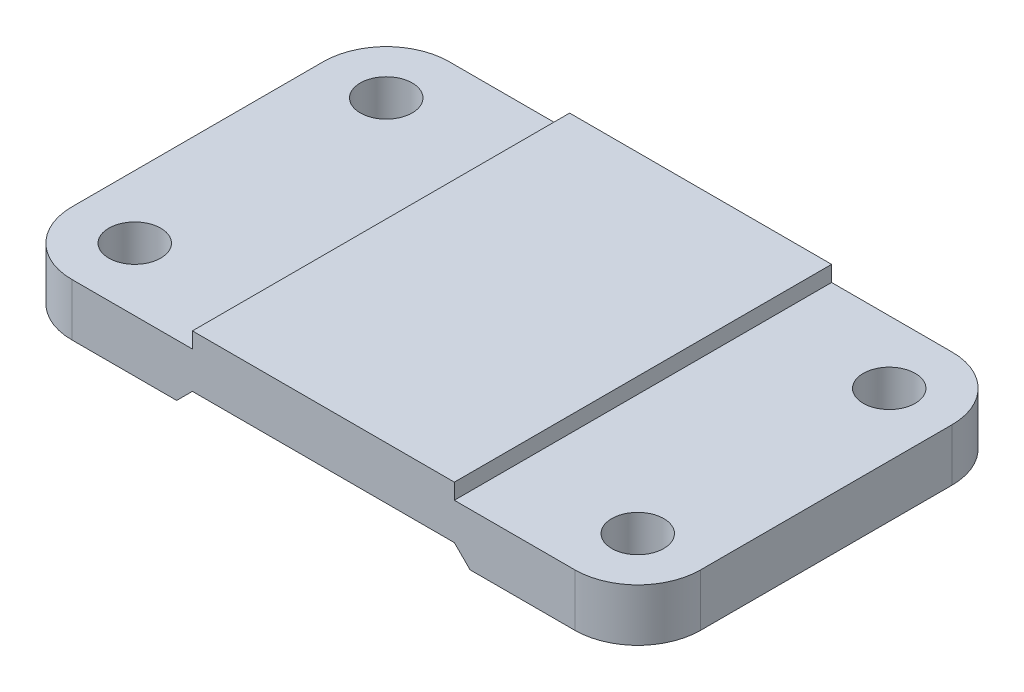
SolidWorks part; units mm, degrees
ref_plane "Front Plane" through (0, 0, 0) normal (0, 0, 1) x (1, 0, 0)
ref_plane "Top Plane" through (0, 0, 0) normal (0, 1, 0) x (1, 0, 0)
ref_plane "Right Plane" through (0, 0, 0) normal (1, 0, 0) x (0, 0, -1)
sketch "Sketch1" plane through (0, 0, 0) normal (0, 1, 0) x (1, 0, 0)
  line L0 (-111.57, 0) -> (84.1985, 0) construction
  line L1 (-60, -36) -> (60, -36)
  line L2 (-60, -36) -> (-60, 36)
  line L3 (-60, 36) -> (60, 36)
  line L4 (60, -36) -> (60, 36)
  line L5 (-60, -36) -> (60, 36) construction
  line L6 (-60, 36) -> (60, -36) construction
  line L7 (0, 48.1132) -> (0, -59.3675) construction
  circle A0 centre (-48, 24) radius 4.9597
  circle A1 centre (48, 24) radius 4.9597
  circle A2 centre (48, -24) radius 4.9597
  circle A3 centre (-48, -24) radius 4.9597
  point P0 (0, 0)
  dimension "D1" = 72
  dimension "D2" = 120
  dimension "D3" = 24
  dimension "D4" = 48
extrude "Boss-Extrude1" add sketch "Sketch1" along normal blind 10
fillet "Fillet1" radius 12 4 edges at (60, 5, 36) (-60, 5, 36) (-60, 5, -36) (60, 5, -36)
sketch "Sketch2" plane through (0, 0, 36) normal (0, 0, 1) x (1, 0, 0)
  line L0 (0, 19.0191) -> (0, -13.0598) construction
  line L1 (0, 0) -> (0, 3)
  line L2 (-48, 0) -> (48, 0) construction
  line L3 (-25, 3) -> (25, 3)
  line L4 (25, 3) -> (28, 0)
  line L5 (28, 0) -> (-28, 0)
  line L6 (-25, 3) -> (-28, 0)
  line M7 (-48, 0) -> (48, 0)
  dimension "D1" = 3
  dimension "D2" = 28
  dimension "D3" = 25
extrude "Cut-Extrude1" cut sketch "Sketch2" against normal blind 73 contours L3 L6 L1 M7 | L4 L3 L1 M7
sketch "Sketch3" plane through (0, 10, 0) normal (0, 1, 0) x (1, 0, 0)
  line L0 (0, 43.453) -> (0, -41.6015) construction
  line L1 (-25, 36) -> (25, 36)
  line L2 (48, 36) -> (-48, 36) construction
  line L3 (25, 36) -> (25, -36)
  line L4 (-48, -36) -> (48, -36) construction
  line L5 (25, -36) -> (-25, -36)
  line L6 (-25, 36) -> (-25, -36)
  point P13 (0, -36)
  point P14 (0, 36)
extrude "Boss-Extrude2" add sketch "Sketch3" along normal blind 3
